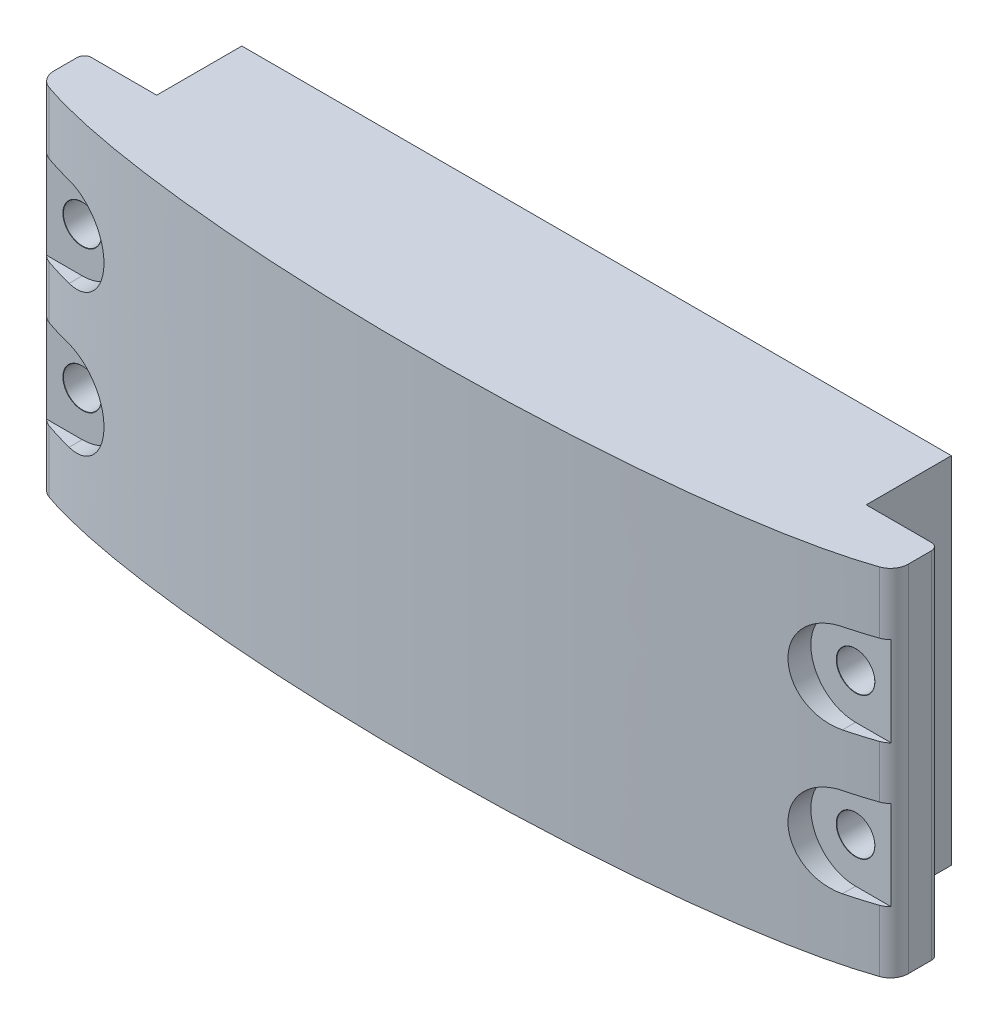
SolidWorks part; units mm, degrees
ref_plane "Front Plane" through (0, 0, 0) normal (0, 0, 1) x (1, 0, 0)
ref_plane "Top Plane" through (0, 0, 0) normal (0, 1, 0) x (1, 0, 0)
ref_plane "Right Plane" through (0, 0, 0) normal (1, 0, 0) x (0, 0, -1)
sketch "Sketch1" plane through (0, 0, 0) normal (0, 1, 0) x (1, 0, 0)
  line L0 (31.75, 0) -> (-31.75, 0)
  line L1 (-31.75, 0) -> (-31.75, -7.62)
  line L2 (-31.75, -7.62) -> (-37.465, -7.62)
  line L3 (31.75, 0) -> (31.75, -7.62)
  line L4 (31.75, -7.62) -> (37.465, -7.62)
  line L7 (-37.465, -7.62) -> (-37.592, -7.62)
  line L8 (-38.227, -8.255) -> (-38.227, -11.43)
  line L11 (37.465, -7.62) -> (37.592, -7.62)
  line L12 (38.227, -8.255) -> (38.227, -11.43)
  arc A0 (-38.227, -8.255) -> (-37.592, -7.62) centre (-37.592, -8.255) cw
  arc A1 (38.227, -8.255) -> (37.592, -7.62) centre (37.592, -8.255) ccw
  arc A2 (38.227, -10.3362) -> (37.1643, -11.8345) centre (36.6395, -10.3362) cw
  arc A3 (-38.227, -10.3362) -> (-37.1643, -11.8345) centre (-36.6395, -10.3362) ccw
  ellipse E0 centre (0, -8.7956) end of major axis (-41.275, -8.7956) minor radius 6.985 (38.227, -11.43) -> (-38.227, -11.43) cw
  point P4 (0, 0)
  point P11 (0, 0)
  point P19 (-38.227, -7.62)
  dimension "D9" = 0.635
  dimension "D10" = 0.635
  dimension "D13" = 1.5875
  dimension "D14" = 1.5875
  dimension "D1" = 63.5
  dimension "D2" = 63.5
  dimension "D3" = 7.62
  dimension "D4" = 5.715
  dimension "D6" = 3.81
  dimension "D8" = 0.762
  dimension "D11" = 0.127
  dimension "D12" = 76.454
  dimension "D5" = 13.97
  dimension "D7" = 3.048
extrude "Boss-Extrude1" add sketch "Sketch1" along normal blind 31.75 contours E0 L12 A1 L11 L4 L3 L0 L1 L2 L7 A0 L8
ref_plane "Plane1" through (0, 0, 11.43) normal (0, 0, 1) x (1, 0, 0)
sketch "Sketch3" plane through (0, 0, 11.43) normal (0, 0, 1) x (1, 0, 0)
  line L0 (-38.227, 31.75) -> (-38.227, 0) construction
  line L1 (-38.227, 26.225) -> (-34.6075, 26.225)
  line L2 (-38.227, 26.225) -> (-38.227, 18.225)
  line L3 (-38.227, 18.225) -> (-34.6075, 18.225)
  line L4 (-34.6075, 26.225) -> (-34.6075, 18.225)
  line L5 (38.227, 31.75) -> (38.227, 0) construction
  line L6 (-38.227, 13.525) -> (-34.6075, 13.525)
  line L7 (-38.227, 13.525) -> (-38.227, 5.525)
  line L8 (-38.227, 5.525) -> (-34.6075, 5.525)
  line L9 (-34.6075, 13.525) -> (-34.6075, 5.525)
  line L10 (38.227, 26.225) -> (34.6075, 26.225)
  line L11 (38.227, 26.225) -> (38.227, 18.225)
  line L12 (38.227, 18.225) -> (34.6075, 18.225)
  line L13 (34.6075, 26.225) -> (34.6075, 18.225)
  line L14 (-37.1643, 0) -> (37.1643, 0) construction
  line L15 (38.227, 13.525) -> (34.6075, 13.525)
  line L16 (38.227, 13.525) -> (38.227, 5.525)
  line L17 (38.227, 5.525) -> (34.6075, 5.525)
  line L18 (34.6075, 13.525) -> (34.6075, 5.525)
  arc A0 (-34.6075, 26.225) -> (-34.6075, 18.225) centre (-34.6075, 22.225) cw
  arc A1 (-34.6075, 13.525) -> (-34.6075, 5.525) centre (-34.6075, 9.525) cw
  arc A2 (34.6075, 26.225) -> (34.6075, 18.225) centre (34.6075, 22.225) ccw
  arc A3 (34.6075, 13.525) -> (34.6075, 5.525) centre (34.6075, 9.525) ccw
  dimension "D1" = 4
  dimension "D2" = 12.7
  dimension "D3" = 9.525
  dimension "D4" = 3.6195
extrude "Cut-Extrude1" cut sketch "Sketch3" along normal through all contours L4 L1 L2 L3 | A0 L4 | L9 L6 L7 L8 | A1 L9 | L15 L18 L17 L16 | L18 A3 | L10 L13 L12 L11 | L13 A2
hole_wizard "M3 Clearance Hole1" positions "Sketch4" profile "Sketch5" hole size "M3" standard "ANSI Metric" end condition through all
sketch "Sketch4" plane through (0, 0, 11.43) normal (0, 0, 1) x (1, 0, 0)
  line L0 (34.6075, 26.225) -> (34.6075, 18.225) construction
  line L1 (34.6075, 13.525) -> (34.6075, 5.525) construction
  point P0 (-34.6075, 22.225)
  point P3 (-34.6075, 9.525)
  point P6 (34.6075, 22.225)
  point P10 (34.6075, 9.525)
sketch "Sketch5" plane through (-34.6075, 22.225, 11.43) normal (1, 0, 0) x (0, -1, 0)
  line L0 (0, 0) -> (0, 11.43)
  line L1 (0, 11.43) -> (1.7, 11.43)
  line L2 (1.7, 11.43) -> (1.7, 0.021)
  line L3 (1.7, 0.021) -> (1.725, 0)
  line L5 (1.725, 0) -> (0, 0)
  line L6 (-1.7, 0.021) -> (-1.725, 0) construction
  line L11 (0, -6.35) -> (0, 107.95) construction
  dimension "Thru Hole Dia." = 3.4
  dimension "Thru Hole Depth" = 11.43
  dimension "Near C'Sink Dia." = 3.45
  dimension "Near C'Sink Angle" = 100
equation "\"Alum plate thickness\"= 0.225"
equation "\"D4@Sketch1\"=\"Alum plate thickness\""
